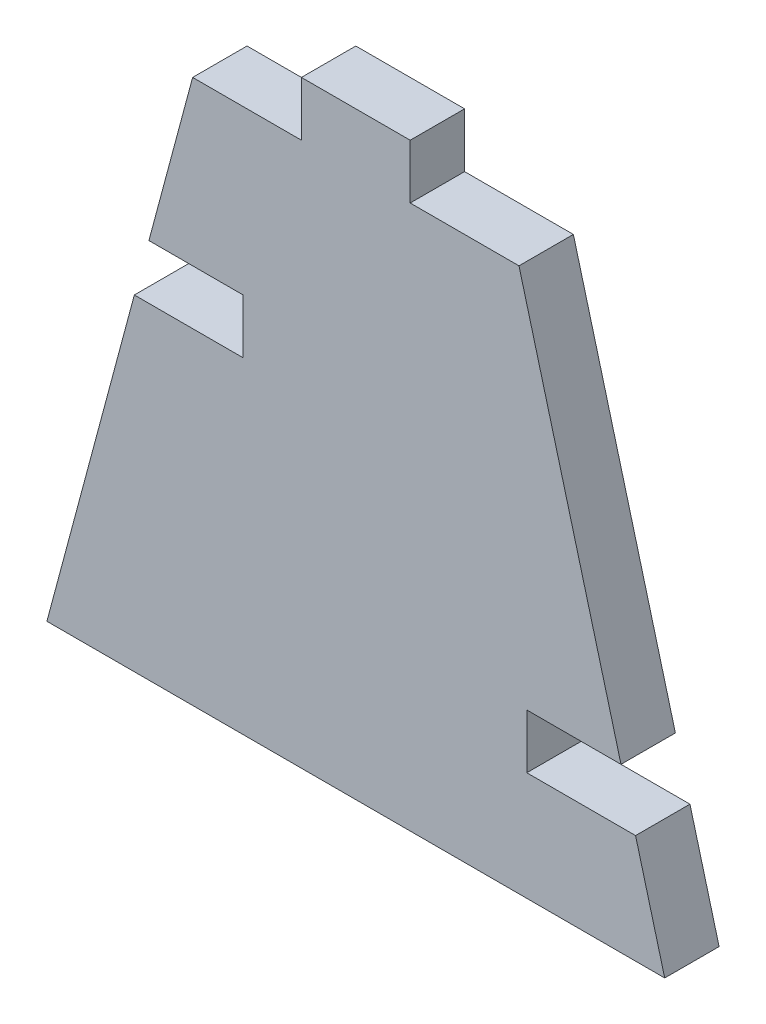
SolidWorks part; units mm, degrees
ref_plane "Front Plane" through (0, 0, 0) normal (0, 0, 1) x (1, 0, 0)
ref_plane "Top Plane" through (0, 0, 0) normal (0, 1, 0) x (1, 0, 0)
ref_plane "Right Plane" through (0, 0, 0) normal (1, 0, 0) x (0, 0, -1)
sketch "Sketch2" plane through (0, 0, 0) normal (0, 0, 1) x (1, 0, 0)
  line L0 (0, 0) -> (20, 0)
  line L1 (20, 0) -> (20, 10)
  line L2 (20, 10) -> (40, 10)
  line L3 (40, 10) -> (40, 0)
  line L4 (40, 0) -> (60, 0)
  line L5 (60, 0) -> (78.7564, -70)
  line L6 (86.7949, -100) -> (-26.7949, -100)
  line L7 (-26.7949, -100) -> (-10.718, -40)
  line L8 (60, 0) -> (60, -100) construction
  line L9 (81.4359, -100) -> (81.4359, -80) construction
  line L10 (81.4359, -80) -> (61.4359, -80)
  line L11 (61.4359, -80) -> (61.4359, -70)
  line L12 (61.4359, -70) -> (78.7564, -70)
  line L13 (81.4359, -80) -> (86.7949, -100)
  line L14 (-10.718, -100) -> (-10.718, -40) construction
  line L15 (-10.718, -40) -> (9.282, -40)
  line L16 (9.282, -40) -> (9.282, -30)
  line L17 (9.282, -30) -> (-8.0385, -30)
  line L18 (-8.0385, -30) -> (0, 0)
  dimension "D1" = 20
  dimension "D2" = 20
  dimension "D3" = 20
  dimension "D4" = 10
  dimension "D5" = 100
  dimension "D6" = 75
  dimension "D7" = 75
  dimension "D8" = 20
  dimension "D9" = 20
  dimension "D10" = 10
  dimension "D11" = 60
  dimension "D12" = 20
  dimension "D13" = 10
extrude "Boss-Extrude1" add sketch "Sketch2" along normal blind 10
